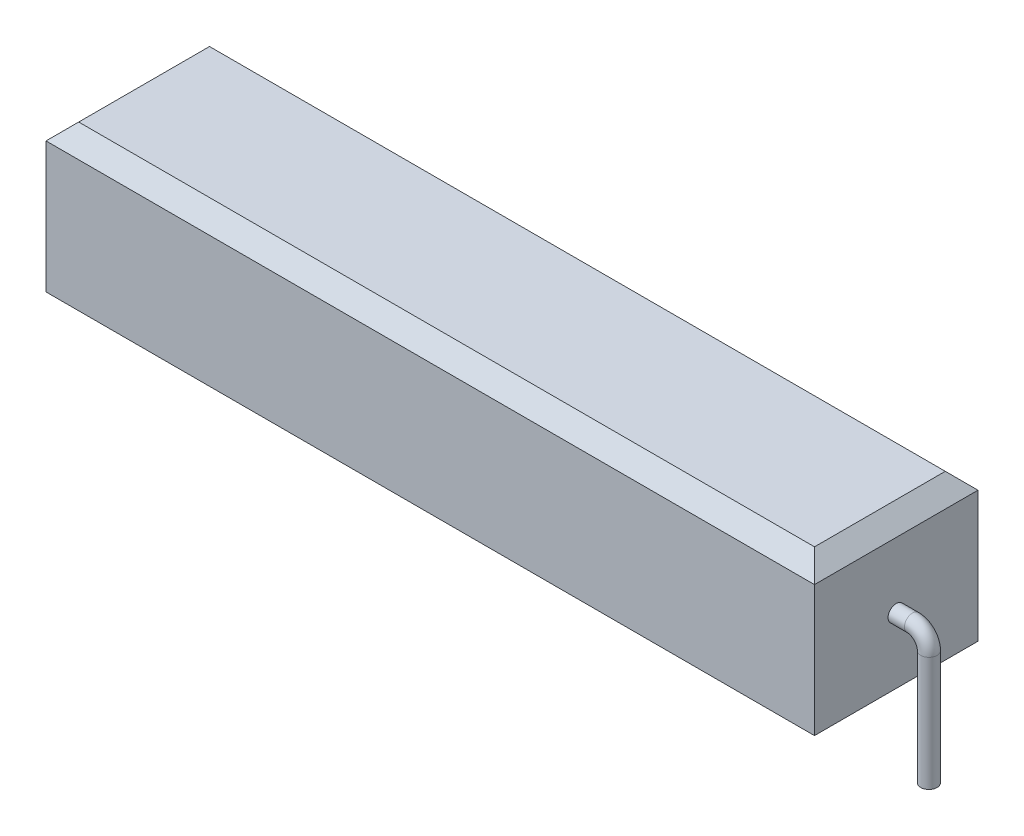
SolidWorks part; units mm, degrees
ref_plane "前视基准面" through (0, 0, 0) normal (0, 0, 1) x (1, 0, 0)
ref_plane "上视基准面" through (0, 0, 0) normal (0, 1, 0) x (1, 0, 0)
ref_plane "右视基准面" through (0, 0, 0) normal (1, 0, 0) x (0, 0, -1)
sketch "草图1" plane through (0, 0, 0) normal (0, 1, 0) x (1, 0, 0)
  line L1 (-23.5, -5) -> (23.5, -5)
  line L2 (-23.5, -5) -> (-23.5, 5)
  line L3 (-23.5, 5) -> (23.5, 5)
  line L4 (23.5, -5) -> (23.5, 5)
  line L5 (-23.5, -5) -> (23.5, 5) construction
  line L6 (-23.5, 5) -> (23.5, -5) construction
  point P0 (0, 0)
  dimension "D1" = 47
  dimension "D2" = 10
extrude "凸台-拉伸1" add sketch "草图1" along normal mid plane 10
chamfer "倒角1" distance 1 angle 45 8 edges at (0, -5, -5) (-23.5, -5, 0) (0, -5, 5) (23.5, -5, 0) (0, 5, 5) (-23.5, 5, 0) (0, 5, -5) (23.5, 5, 0)
sketch "草图2" plane through (0, 0, 0) normal (0, 0, 1) x (1, 0, 0)
  line L0 (23.5, 0) -> (24.5, 0)
  line L1 (23.5, 4) -> (23.5, -4) construction
  line L2 (25.5, -1) -> (25.5, -8)
  arc A0 (24.5, 0) -> (25.5, -1) centre (24.5, -1) cw
  point P8 (25.5, 0)
  dimension "D3" = 1
  dimension "D1" = 2
  dimension "D2" = 8
sweep "扫描1" add path "草图2" circular profile diameter 1 parameters "D3"=1
sketch "草图9" plane through (0, 0, 0) normal (0, 0, 1) x (1, 0, 0)
  line L0 (-23.5, 0) -> (-24.5, 0)
  line L1 (-23.5, 4) -> (-23.5, -4) construction
  line L2 (-25.5, -1) -> (-25.5, -8)
  arc A0 (-24.5, 0) -> (-25.5, -1) centre (-24.5, -1) ccw
  point P8 (-25.5, 0)
  dimension "D3" = 1
  dimension "D1" = 8
  dimension "D2" = 2
sweep "扫描2" add path "草图9" circular profile diameter 1 parameters "D3"=1
sketch "草图16" plane through (0, -8, 0) normal (0, -1, 0) x (-1, 0, 0)
  point P0 (25.5, 0)
  point P1 (-25.5, 0)
  dimension "D1" = 51
